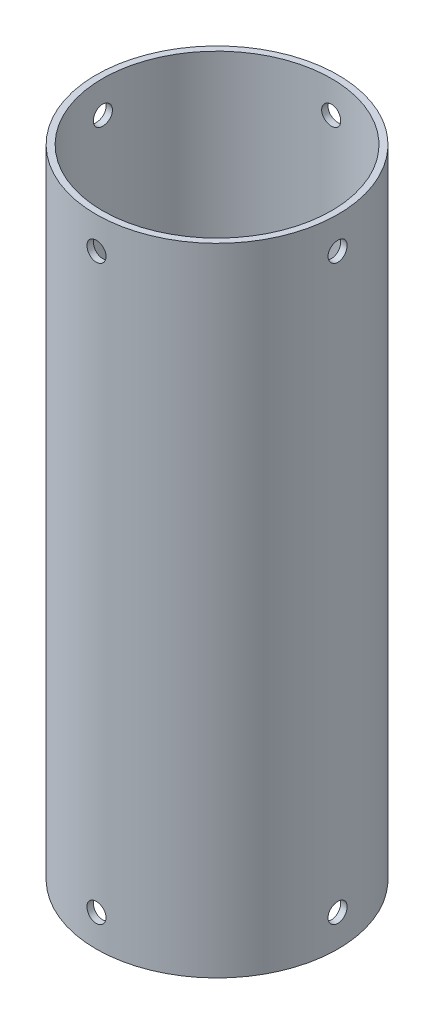
SolidWorks part; units mm, degrees
material "Hexcel AS4C (3000 Filaments)"
ref_plane "Front Plane" through (0, 0, 0) normal (0, 0, 1) x (1, 0, 0)
ref_plane "Top Plane" through (0, 0, 0) normal (0, 1, 0) x (1, 0, 0)
ref_plane "Right Plane" through (0, 0, 0) normal (1, 0, 0) x (0, 0, -1)
sketch "Sketch1" plane through (0, 0, 0) normal (0, 1, 0) x (1, 0, 0)
  circle A0 centre (0, 0) radius 19
  circle A1 centre (0, 0) radius 18
  dimension "D1" = 38
  dimension "D2" = 1
extrude "Boss-Extrude1" add sketch "Sketch1" along normal blind 100
sketch "Sketch2" plane through (0, 0, 0) normal (0, 0, 1) x (1, 0, 0)
  line L0 (0, 100) -> (0, 0) construction
  line L1 (19, 100) -> (-19, 100) construction
  line L3 (-19, 0) -> (19, 0) construction
  circle A1 centre (0, 95) radius 1.5
  circle A2 centre (0, 5) radius 1.5
  dimension "D1" = 3
  dimension "D2" = 3
  dimension "D5" = 0
  dimension "D4" = 5
  dimension "D3" = 5
extrude "Cut-Extrude1" cut sketch "Sketch2" against normal through all and the other way through all
sketch "Sketch3" plane through (0, 0, 0) normal (1, 0, 0) x (0, 0, -1)
  line L0 (0, 100) -> (0, 0) construction
  line L1 (18, 100) -> (-18, 100) construction
  line L2 (-19, 0) -> (19, 0) construction
  line L3 (19, 100) -> (-19, 100) construction
  circle A0 centre (0, 5) radius 1.5
  circle A1 centre (0, 95) radius 1.5
  dimension "D1" = 3
  dimension "D2" = 3
  dimension "D3" = 5
  dimension "D4" = 5
extrude "Cut-Extrude2" cut sketch "Sketch3" against normal through all and the other way through all
